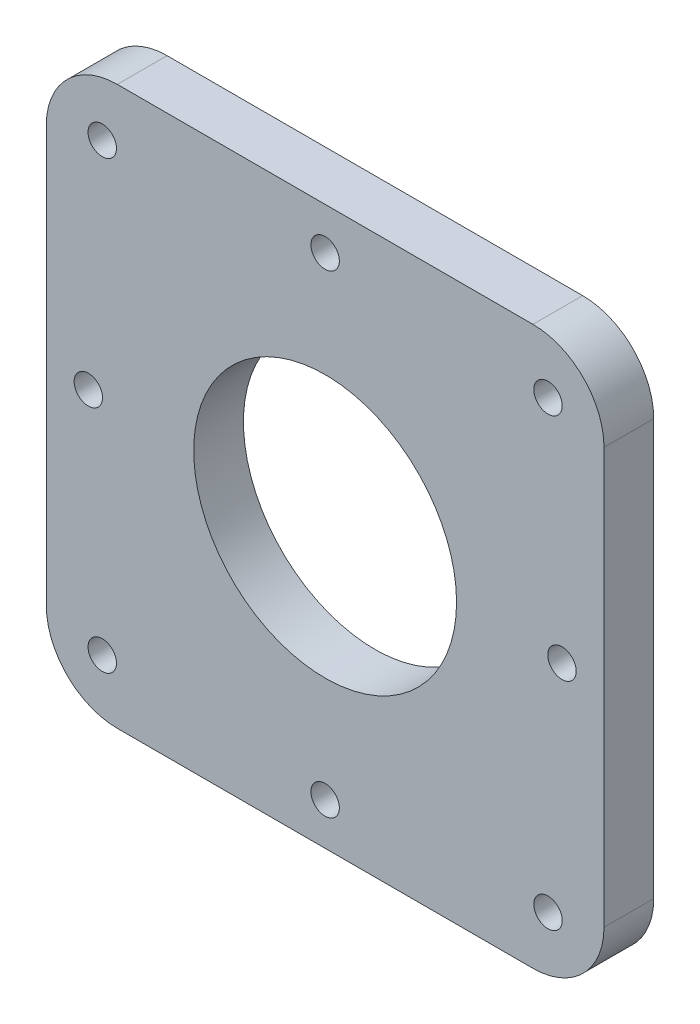
SolidWorks part; units mm, degrees
material "ABS"
ref_plane "Front Plane" through (0, 0, 0) normal (0, 0, 1) x (1, 0, 0)
ref_plane "Top Plane" through (0, 0, 0) normal (0, 1, 0) x (1, 0, 0)
ref_plane "Right Plane" through (0, 0, 0) normal (1, 0, 0) x (0, 0, -1)
sketch "Sketch1" plane through (0, 0, 0) normal (0, 0, 1) x (1, 0, 0)
  line L1 (-39.25, -39.25) -> (39.25, -39.25)
  line L2 (-39.25, -39.25) -> (-39.25, 39.25)
  line L3 (-39.25, 39.25) -> (39.25, 39.25)
  line L4 (39.25, -39.25) -> (39.25, 39.25)
  line L5 (-39.25, -39.25) -> (39.25, 39.25) construction
  line L6 (-39.25, 39.25) -> (39.25, -39.25) construction
  point P0 (0, 0)
  dimension "D1" = 78.5
extrude "Boss-Extrude1" add sketch "Sketch1" along normal mid plane 7
fillet "Fillet1" radius 10 4 edges at (-39.25, -39.25, 0) (39.25, -39.25, 0) (39.25, 39.25, 0) (-39.25, 39.25, 0)
sketch "Sketch2" plane through (0, 0, 3.5) normal (0, 0, 1) x (1, 0, 0)
  line L0 (0, 0) -> (-35355.3391, 35355.3391) construction
  line L1 (0, 0) -> (0, 50000) construction
  line L2 (0, 0) -> (-50000, 0) construction
  circle A0 centre (-31.3713, 31.3713) radius 2
  arc A8 (-29.25, 39.25) -> (-39.25, 29.25) centre (-29.25, 29.25) ccw construction
  circle A9 centre (-31.3713, -31.3713) radius 2
  circle A10 centre (31.3713, 31.3713) radius 2
  circle A11 centre (31.3713, -31.3713) radius 2
  dimension "D2" = 4
  dimension "D3" = 3
  dimension "D1" = 45
extrude "Cut-Extrude1" cut sketch "Sketch2" against normal through all
sketch "Sketch3" plane through (0, 0, 3.5) normal (0, 0, 1) x (1, 0, 0)
  circle A0 centre (0, 0) radius 18.5
  dimension "D1" = 37
extrude "Cut-Extrude2" cut sketch "Sketch3" against normal through all
sketch "Sketch4" plane through (0, 0, 3.5) normal (0, 0, 1) x (1, 0, 0)
  line L0 (0, 0) -> (0, 18.5) construction
  line L1 (0, -33.333) -> (33.333, 0) construction
  line L2 (0, -33.333) -> (-33.333, 0) construction
  line L3 (-33.333, 0) -> (0, 33.333) construction
  line L4 (33.333, 0) -> (0, 33.333) construction
  line L5 (0, -33.333) -> (0, 33.333) construction
  line L6 (-33.333, 0) -> (33.333, 0) construction
  circle A0 centre (0, 33.333) radius 2
  circle A1 centre (-33.333, 0) radius 2
  circle A2 centre (0, -33.333) radius 2
  circle A3 centre (33.333, 0) radius 2
  circle A4 centre (0, 0) radius 18.5 construction
  point P0 (0, 0)
  dimension "D2" = 4
  dimension "D1" = 47.14
extrude "Cut-Extrude3" cut sketch "Sketch4" against normal through all
